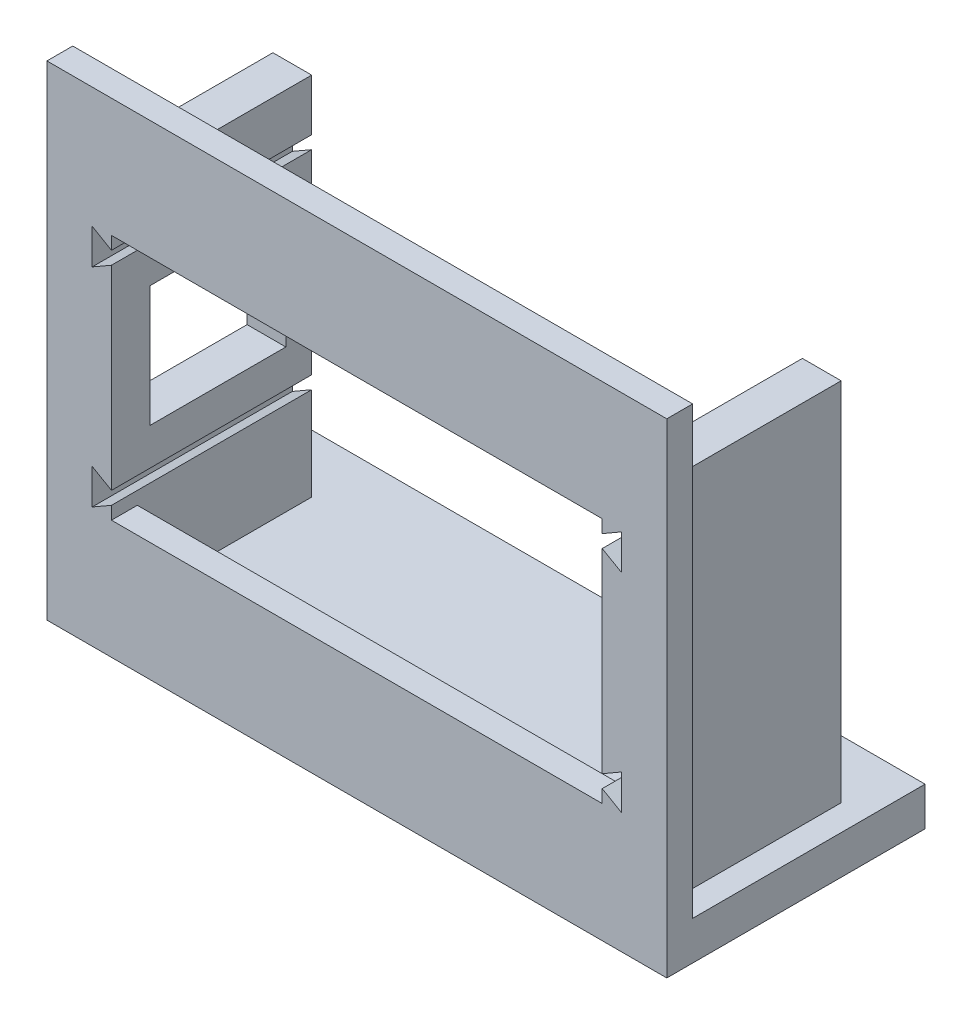
SolidWorks part; units mm, degrees
ref_plane "Front Plane" through (0, 0, 0) normal (0, 0, 1) x (1, 0, 0)
ref_plane "Top Plane" through (0, 0, 0) normal (0, 1, 0) x (1, 0, 0)
ref_plane "Right Plane" through (0, 0, 0) normal (1, 0, 0) x (0, 0, -1)
sketch "Sketch2" plane through (0, 0, 0) normal (0, 1, 0) x (1, 0, 0)
  line L1 (-100, 75) -> (100, 75)
  line L2 (-100, 75) -> (-100, -75)
  line L3 (-100, -75) -> (100, -75)
  line L4 (100, 75) -> (100, -75)
  line L5 (-100, 75) -> (100, -75) construction
  line L6 (-100, -75) -> (100, 75) construction
  point P0 (0, 0)
  dimension "D1" = 200
  dimension "D2" = 150
extrude "Boss-Extrude1" add sketch "Sketch2" along normal blind 80
fillet "Fillet1" radius 10 4 edges at (-100, 40, -75) (100, 40, -75) (100, 40, 75) (-100, 40, 75)
shell "Shell1" thickness 2
sketch "Sketch5" plane through (0, 0, 75) normal (0, 0, 1) x (1, 0, 0)
  line L1 (-18.25, 44.5) -> (18.25, 44.5)
  line L2 (-18.25, 44.5) -> (-18.25, 17)
  line L3 (-18.25, 17) -> (18.25, 17)
  line L4 (18.25, 44.5) -> (18.25, 17)
  line L5 (-18.25, 43.5) -> (-19.75, 44.366)
  line L6 (-19.75, 44.366) -> (-19.75, 41.634)
  line L7 (-19.75, 41.634) -> (-18.25, 42.5)
  line L8 (-18.25, 42.5) -> (-18.25, 43.5)
  line L9 (0, 44.5) -> (0, 17) construction
  line L10 (-18.25, 30.75) -> (18.25, 30.75) construction
  line L11 (-19.75, 19.866) -> (-18.25, 19)
  line L12 (-19.75, 17.134) -> (-19.75, 19.866)
  line L13 (-18.25, 18) -> (-19.75, 17.134)
  line L14 (-18.25, 19) -> (-18.25, 18)
  line L15 (19.75, 17.134) -> (19.75, 19.866)
  line L16 (18.25, 18) -> (19.75, 17.134)
  line L17 (18.25, 19) -> (18.25, 18)
  line L18 (19.75, 19.866) -> (18.25, 19)
  line L19 (19.75, 41.634) -> (18.25, 42.5)
  line L20 (19.75, 44.366) -> (19.75, 41.634)
  line L21 (18.25, 43.5) -> (19.75, 44.366)
  line L22 (18.25, 42.5) -> (18.25, 43.5)
  line L23 (-90, 15) -> (90, 15) construction
  point P4 (0, 17)
  dimension "D1" = 36.5
  dimension "D2" = 27.5
  dimension "D3" = 60
  dimension "D4" = 60
  dimension "D5" = 1
  dimension "D6" = 1
  dimension "D7" = 1.5
  dimension "D8" = 2
extrude "Cut-Extrude1" cut sketch "Sketch5" against normal up to surface (2 mm away) contours L1 L4 L3 L2 | L7 L8 L5 L6 | L12 L11 L14 L13 | L20 L19 L22 L21 | L15 L18 L17 L16 up to face at (0, 47.5, 73)
sketch "Sketch6" plane through (0, 0, 73) normal (0, 0, -1) x (-1, 0, 0)
  line L0 (18.25, 15) -> (21.25, 15)
  line L2 (-21.25, 47.5) -> (-21.25, 15)
  line L4 (19.75, 44.366) -> (18.25, 43.5)
  line L5 (19.75, 41.634) -> (19.75, 44.366)
  line L6 (18.25, 42.5) -> (19.75, 41.634)
  line L7 (18.25, 43.5) -> (18.25, 42.5)
  line L8 (19.75, 44.366) -> (18.25, 43.5)
  line L9 (19.75, 41.634) -> (19.75, 44.366)
  line L10 (18.25, 42.5) -> (19.75, 41.634)
  line L12 (18.25, 44.5) -> (-18.25, 44.5)
  line L13 (-18.25, 44.5) -> (-18.25, 17)
  line L14 (-18.25, 17) -> (18.25, 17)
  line L15 (18.25, 17) -> (18.25, 44.5)
  line L17 (-18.25, 47.5) -> (-18.25, 43.5)
  line L19 (18.25, 15) -> (18.25, 18)
  line L20 (-19.75, 41.634) -> (-18.25, 42.5)
  line L21 (-18.25, 42.5) -> (-18.25, 43.5)
  line L22 (-18.25, 43.5) -> (-19.75, 44.366)
  line L23 (-19.75, 44.366) -> (-19.75, 41.634)
  line L24 (-19.75, 41.634) -> (-18.25, 42.5)
  line L26 (-18.25, 43.5) -> (-19.75, 44.366)
  line L27 (-19.75, 44.366) -> (-19.75, 41.634)
  line L28 (-19.75, 19.866) -> (-19.75, 17.134)
  line L29 (-18.25, 19) -> (-19.75, 19.866)
  line L30 (-18.25, 18) -> (-18.25, 19)
  line L31 (-19.75, 17.134) -> (-18.25, 18)
  line L32 (-19.75, 19.866) -> (-19.75, 17.134)
  line L33 (-18.25, 19) -> (-19.75, 19.866)
  line L35 (-19.75, 17.134) -> (-18.25, 18)
  line L36 (19.75, 19.866) -> (18.25, 19)
  line L37 (18.25, 19) -> (18.25, 18)
  line L38 (18.25, 18) -> (19.75, 17.134)
  line L39 (19.75, 17.134) -> (19.75, 19.866)
  line L40 (19.75, 19.866) -> (18.25, 19)
  line L42 (18.25, 18) -> (19.75, 17.134)
  line L43 (19.75, 17.134) -> (19.75, 19.866)
  line L44 (21.25, 47.5) -> (21.25, 15)
  line L45 (-18.25, 15) -> (-21.25, 15)
  line L46 (-18.25, 42.5) -> (-18.25, 19)
  line L47 (18.25, 43.5) -> (18.25, 47.5)
  line L48 (18.25, 19) -> (18.25, 42.5)
  line L49 (-18.25, 18) -> (-18.25, 15)
  line L50 (21.25, 47.5) -> (18.25, 47.5)
  line L51 (-21.25, 47.5) -> (-18.25, 47.5)
  line L54 (18.25, 44.5) -> (-18.25, 44.5) construction
  line L55 (90, 15) -> (-90, 15) construction
  dimension "D6" = 3
  dimension "D7" = 3
  dimension "D8" = 3
  dimension "D1" = 0
  dimension "D2" = 0
  dimension "D3" = 0
  dimension "D4" = 0
  dimension "D5" = 0
extrude "Boss-Extrude2" add sketch "Sketch6" along normal blind 16
sketch "Sketch7" plane through (100, 0, 0) normal (1, 0, 0) x (0, 0, -1)
  line L0 (-65, 15) -> (65, 15) construction
  line L1 (-18.25, 44.5) -> (18.25, 44.5)
  line L2 (-18.25, 44.5) -> (-18.25, 17)
  line L3 (-18.25, 17) -> (18.25, 17)
  line L4 (18.25, 44.5) -> (18.25, 17)
  line L5 (-18.25, 43.5) -> (-19.75, 44.366)
  line L6 (-19.75, 44.366) -> (-19.75, 41.634)
  line L7 (-19.75, 41.634) -> (-18.25, 42.5)
  line L8 (-18.25, 42.5) -> (-18.25, 43.5)
  line L9 (0, 44.5) -> (0, 17) construction
  line L10 (-18.25, 30.75) -> (18.25, 30.75) construction
  line L11 (-19.75, 19.866) -> (-18.25, 19)
  line L12 (-19.75, 17.134) -> (-19.75, 19.866)
  line L13 (-18.25, 18) -> (-19.75, 17.134)
  line L14 (-18.25, 19) -> (-18.25, 18)
  line L15 (19.75, 17.134) -> (19.75, 19.866)
  line L16 (18.25, 18) -> (19.75, 17.134)
  line L17 (18.25, 19) -> (18.25, 18)
  line L18 (19.75, 19.866) -> (18.25, 19)
  line L19 (19.75, 41.634) -> (18.25, 42.5)
  line L20 (19.75, 44.366) -> (19.75, 41.634)
  line L21 (18.25, 43.5) -> (19.75, 44.366)
  line L22 (18.25, 42.5) -> (18.25, 43.5)
  dimension "D1" = 36.5
  dimension "D2" = 27.5
  dimension "D3" = 60
  dimension "D4" = 60
  dimension "D5" = 1
  dimension "D6" = 1
  dimension "D7" = 1.5
  dimension "D8" = 2
extrude "Cut-Extrude2" cut sketch "Sketch7" against normal blind 2 contours L1 L4 L3 L2 | L7 L8 L5 L6 | L12 L11 L14 L13 | L20 L19 L22 L21 | L15 L18 L17 L16
sketch "Sketch8" plane through (98, 0, 0) normal (-1, 0, 0) x (0, 0, 1)
  line L0 (65, 15) -> (-65, 15) construction
  line L1 (-21.25, 47.5) -> (-18.25, 47.5)
  line L2 (-21.25, 47.5) -> (-21.25, 15)
  line L3 (-21.25, 15) -> (-18.25, 15)
  line L4 (19.75, 44.366) -> (18.25, 43.5)
  line L5 (19.75, 41.634) -> (19.75, 44.366)
  line L6 (18.25, 42.5) -> (19.75, 41.634)
  line L7 (18.25, 43.5) -> (18.25, 42.5)
  line L8 (19.75, 44.366) -> (18.25, 43.5)
  line L9 (19.75, 41.634) -> (19.75, 44.366)
  line L10 (18.25, 42.5) -> (19.75, 41.634)
  line L20 (-19.75, 41.634) -> (-18.25, 42.5)
  line L21 (-18.25, 42.5) -> (-18.25, 43.5)
  line L22 (-18.25, 43.5) -> (-19.75, 44.366)
  line L23 (-19.75, 44.366) -> (-19.75, 41.634)
  line L24 (-19.75, 41.634) -> (-18.25, 42.5)
  line L26 (-18.25, 43.5) -> (-19.75, 44.366)
  line L27 (-19.75, 44.366) -> (-19.75, 41.634)
  line L28 (-19.75, 19.866) -> (-19.75, 17.134)
  line L29 (-18.25, 19) -> (-19.75, 19.866)
  line L30 (-18.25, 18) -> (-18.25, 19)
  line L31 (-19.75, 17.134) -> (-18.25, 18)
  line L32 (-19.75, 19.866) -> (-19.75, 17.134)
  line L33 (-18.25, 19) -> (-19.75, 19.866)
  line L35 (-19.75, 17.134) -> (-18.25, 18)
  line L36 (19.75, 19.866) -> (18.25, 19)
  line L37 (18.25, 19) -> (18.25, 18)
  line L38 (18.25, 18) -> (19.75, 17.134)
  line L39 (19.75, 17.134) -> (19.75, 19.866)
  line L40 (19.75, 19.866) -> (18.25, 19)
  line L42 (18.25, 18) -> (19.75, 17.134)
  line L43 (19.75, 17.134) -> (19.75, 19.866)
  line L44 (-18.25, 47.5) -> (-18.25, 43.5)
  line L46 (-18.25, 42.5) -> (-18.25, 19) construction
  line L47 (18.25, 44.5) -> (-18.25, 44.5) construction
  line L48 (-18.25, 42.5) -> (-18.25, 19)
  line L49 (-18.25, 18) -> (-18.25, 15)
  line L50 (18.25, 42.5) -> (18.25, 19) construction
  line L51 (18.25, 47.5) -> (21.25, 47.5)
  line L52 (18.25, 47.5) -> (18.25, 43.5)
  line L53 (18.25, 15) -> (21.25, 15)
  line L54 (21.25, 47.5) -> (21.25, 15)
  line L55 (18.25, 42.5) -> (18.25, 19)
  line L56 (18.25, 18) -> (18.25, 15)
  dimension "D6" = 3
  dimension "D7" = 3
  dimension "D2" = 3
  dimension "D1" = 0
  dimension "D3" = 0
  dimension "D4" = 0
  dimension "D5" = 0
extrude "Boss-Extrude3" add sketch "Sketch8" along normal blind 16
sketch "Sketch10" plane through (-100, 0, 0) normal (-1, 0, 0) x (0, 0, 1)
  line L1 (-18.25, 44.5) -> (18.25, 44.5)
  line L2 (-18.25, 44.5) -> (-18.25, 17)
  line L3 (-18.25, 17) -> (18.25, 17)
  line L4 (18.25, 44.5) -> (18.25, 17)
  line L5 (-18.25, 43.5) -> (-19.75, 44.366)
  line L6 (-19.75, 44.366) -> (-19.75, 41.634)
  line L7 (-19.75, 41.634) -> (-18.25, 42.5)
  line L8 (-18.25, 42.5) -> (-18.25, 43.5)
  line L9 (0, 44.5) -> (0, 17) construction
  line L10 (-18.25, 30.75) -> (18.25, 30.75) construction
  line L11 (-19.75, 19.866) -> (-18.25, 19)
  line L12 (-19.75, 17.134) -> (-19.75, 19.866)
  line L13 (-18.25, 18) -> (-19.75, 17.134)
  line L14 (-18.25, 19) -> (-18.25, 18)
  line L15 (19.75, 17.134) -> (19.75, 19.866)
  line L16 (18.25, 18) -> (19.75, 17.134)
  line L17 (18.25, 19) -> (18.25, 18)
  line L18 (19.75, 19.866) -> (18.25, 19)
  line L19 (19.75, 41.634) -> (18.25, 42.5)
  line L20 (19.75, 44.366) -> (19.75, 41.634)
  line L21 (18.25, 43.5) -> (19.75, 44.366)
  line L22 (18.25, 42.5) -> (18.25, 43.5)
  line L23 (-65, 15) -> (65, 15) construction
  dimension "D1" = 36.5
  dimension "D2" = 27.5
  dimension "D3" = 60
  dimension "D4" = 60
  dimension "D5" = 1
  dimension "D6" = 1
  dimension "D7" = 1.5
  dimension "D8" = 2
extrude "Cut-Extrude4" cut sketch "Sketch10" against normal blind 2 contours L1 L4 L3 L2 | L7 L8 L5 L6 | L12 L11 L14 L13 | L20 L19 L22 L21 | L15 L18 L17 L16
sketch "Sketch11" plane through (-98, 0, 0) normal (1, 0, 0) x (0, 0, -1)
  line L1 (-18.25, 42.5) -> (-18.25, 19) construction
  line L2 (-18.25, 47.5) -> (-21.25, 47.5)
  line L3 (-18.25, 47.5) -> (-18.25, 43.5)
  line L4 (19.75, 44.366) -> (18.25, 43.5)
  line L5 (19.75, 41.634) -> (19.75, 44.366)
  line L6 (18.25, 42.5) -> (19.75, 41.634)
  line L7 (18.25, 43.5) -> (18.25, 42.5)
  line L8 (19.75, 44.366) -> (18.25, 43.5)
  line L9 (19.75, 41.634) -> (19.75, 44.366)
  line L10 (18.25, 42.5) -> (19.75, 41.634)
  line L20 (-19.75, 41.634) -> (-18.25, 42.5)
  line L21 (-18.25, 42.5) -> (-18.25, 43.5)
  line L22 (-18.25, 43.5) -> (-19.75, 44.366)
  line L23 (-19.75, 44.366) -> (-19.75, 41.634)
  line L24 (-19.75, 41.634) -> (-18.25, 42.5)
  line L26 (-18.25, 43.5) -> (-19.75, 44.366)
  line L27 (-19.75, 44.366) -> (-19.75, 41.634)
  line L28 (-19.75, 19.866) -> (-19.75, 17.134)
  line L29 (-18.25, 19) -> (-19.75, 19.866)
  line L30 (-18.25, 18) -> (-18.25, 19)
  line L31 (-19.75, 17.134) -> (-18.25, 18)
  line L32 (-19.75, 19.866) -> (-19.75, 17.134)
  line L33 (-18.25, 19) -> (-19.75, 19.866)
  line L35 (-19.75, 17.134) -> (-18.25, 18)
  line L36 (19.75, 19.866) -> (18.25, 19)
  line L37 (18.25, 19) -> (18.25, 18)
  line L38 (18.25, 18) -> (19.75, 17.134)
  line L39 (19.75, 17.134) -> (19.75, 19.866)
  line L40 (19.75, 19.866) -> (18.25, 19)
  line L42 (18.25, 18) -> (19.75, 17.134)
  line L43 (19.75, 17.134) -> (19.75, 19.866)
  line L44 (-18.25, 15) -> (-21.25, 15)
  line L45 (-21.25, 47.5) -> (-21.25, 15)
  line L46 (65, 15) -> (-65, 15) construction
  line L47 (18.25, 44.5) -> (-18.25, 44.5) construction
  line L48 (-18.25, 42.5) -> (-18.25, 19)
  line L49 (-18.25, 18) -> (-18.25, 15)
  line L50 (18.25, 42.5) -> (18.25, 19) construction
  line L51 (18.25, 47.5) -> (21.25, 47.5)
  line L52 (18.25, 47.5) -> (18.25, 43.5)
  line L53 (18.25, 15) -> (21.25, 15)
  line L54 (21.25, 47.5) -> (21.25, 15)
  line L55 (18.25, 42.5) -> (18.25, 19)
  line L56 (18.25, 18) -> (18.25, 15)
  dimension "D2" = 3
  dimension "D6" = 3
  dimension "D7" = 3
  dimension "D1" = 0
  dimension "D3" = 0
  dimension "D4" = 0
  dimension "D5" = 0
extrude "Boss-Extrude4" add sketch "Sketch11" along normal blind 16
sketch "Sketch13" plane through (0, 0, 75) normal (0, 0, 1) x (1, 0, 0)
  line L0 (-18.25, 30.75) -> (18.25, 30.75) construction
  line L1 (-18.25, 30.75) -> (18.25, 30.75) construction
  line L2 (41, 39.3) -> (39.5, 40.166)
  line L3 (41, 40.3) -> (79, 40.3)
  line L4 (41, 40.3) -> (41, 21.2)
  line L5 (41, 21.2) -> (79, 21.2)
  line L6 (79, 40.3) -> (79, 21.2)
  line L7 (39.5, 40.166) -> (39.5, 37.434)
  line L8 (39.5, 37.434) -> (41, 38.3)
  line L9 (41, 39.3) -> (41, 38.3)
  line L10 (60, 40.3) -> (60, 21.2) construction
  line L11 (41, 22.2) -> (39.5, 21.334)
  line L12 (39.5, 21.334) -> (39.5, 24.066)
  line L13 (39.5, 24.066) -> (41, 23.2)
  line L14 (41, 22.2) -> (41, 23.2)
  line L15 (79, 22.2) -> (79, 23.2)
  line L16 (80.5, 24.066) -> (79, 23.2)
  line L17 (80.5, 21.334) -> (80.5, 24.066)
  line L18 (79, 22.2) -> (80.5, 21.334)
  line L19 (79, 39.3) -> (80.5, 40.166)
  line L20 (80.5, 40.166) -> (80.5, 37.434)
  line L21 (80.5, 37.434) -> (79, 38.3)
  line L22 (79, 39.3) -> (79, 38.3)
  point P6 (41, 30.75)
  point P7 (60, 21.2)
  dimension "D1" = 19.1
  dimension "D2" = 38
  dimension "D3" = 60
  dimension "D4" = 60
  dimension "D5" = 60
  dimension "D6" = 1
  dimension "D7" = 1
  dimension "D8" = 1.5
extrude "Cut-Extrude5" cut sketch "Sketch13" against normal up to surface (2 mm away) contours L3 L6 L5 L4 | L7 L8 L9 L2 | L12 L13 L14 L11 | L17 L16 L15 L18 | L20 L21 L22 L19 up to face at (0, 41.5833, 73)
sketch "Sketch14" plane through (0, 0, 73) normal (0, 0, -1) x (-1, 0, 0)
  line L0 (-21.25, 15) -> (-90, 15) construction
  line L1 (-79, 43.3) -> (-82, 43.3)
  line L2 (-79, 43.3) -> (-79, 39.3)
  line L3 (-79, 15) -> (-82, 15)
  line L6 (-82, 43.3) -> (-82, 15)
  line L12 (-39.5, 40.166) -> (-41, 39.3)
  line L13 (-39.5, 37.434) -> (-39.5, 40.166)
  line L14 (-41, 38.3) -> (-39.5, 37.434)
  line L15 (-41, 39.3) -> (-41, 38.3)
  line L16 (-39.5, 40.166) -> (-41, 39.3)
  line L17 (-39.5, 37.434) -> (-39.5, 40.166)
  line L18 (-41, 38.3) -> (-39.5, 37.434)
  line L20 (-79, 39.3) -> (-80.5, 40.166)
  line L21 (-80.5, 40.166) -> (-80.5, 37.434)
  line L22 (-80.5, 37.434) -> (-79, 38.3)
  line L23 (-79, 38.3) -> (-79, 39.3)
  line L24 (-79, 39.3) -> (-80.5, 40.166)
  line L25 (-80.5, 40.166) -> (-80.5, 37.434)
  line L26 (-80.5, 37.434) -> (-79, 38.3)
  line L28 (-79, 22.2) -> (-79, 23.2)
  line L29 (-79, 23.2) -> (-80.5, 24.066)
  line L30 (-80.5, 24.066) -> (-80.5, 21.334)
  line L31 (-80.5, 21.334) -> (-79, 22.2)
  line L33 (-79, 23.2) -> (-80.5, 24.066)
  line L34 (-80.5, 24.066) -> (-80.5, 21.334)
  line L35 (-80.5, 21.334) -> (-79, 22.2)
  line L36 (-39.5, 21.334) -> (-39.5, 24.066)
  line L37 (-39.5, 24.066) -> (-41, 23.2)
  line L38 (-41, 23.2) -> (-41, 22.2)
  line L39 (-41, 22.2) -> (-39.5, 21.334)
  line L40 (-39.5, 21.334) -> (-39.5, 24.066)
  line L41 (-39.5, 24.066) -> (-41, 23.2)
  line L43 (-41, 22.2) -> (-39.5, 21.334)
  line L44 (-41, 40.3) -> (-79, 40.3) construction
  line L45 (-41, 43.3) -> (-38, 43.3)
  line L46 (-41, 43.3) -> (-41, 39.3)
  line L47 (-41, 15) -> (-38, 15)
  line L48 (-38, 43.3) -> (-38, 15)
  line L49 (-79, 38.3) -> (-79, 23.2) construction
  line L50 (-41, 38.3) -> (-41, 23.2) construction
  line L51 (-79, 38.3) -> (-79, 23.2)
  line L52 (-79, 22.2) -> (-79, 15)
  line L53 (-41, 38.3) -> (-41, 23.2)
  line L54 (-41, 22.2) -> (-41, 15)
  dimension "D1" = 3
  dimension "D6" = 3
  dimension "D7" = 3
  dimension "D2" = 0
  dimension "D3" = 0
  dimension "D4" = 0
  dimension "D5" = 0
extrude "Boss-Extrude5" add sketch "Sketch14" along normal blind 13.5
sketch "Sketch15" plane through (38, 0, 0) normal (-1, 0, 0) x (0, 0, 1)
  line L4 (59.5, 15) -> (59.5, 43.3) construction
  line L5 (73, 15) -> (73, 43.3) construction
  line L6 (59.5, 43.3) -> (59.5, 15) construction
  line L7 (59.5, 37.434) -> (75, 37.434) construction
  line L8 (59.5, 24.066) -> (75, 24.066) construction
  line L12 (72, 26.066) -> (72, 35.434)
  line L13 (72, 35.434) -> (61.5, 35.434)
  line L14 (61.5, 35.434) -> (61.5, 26.066)
  line L15 (61.5, 26.066) -> (72, 26.066)
  dimension "D1" = 2
  dimension "D2" = 1
  dimension "D3" = 2
  dimension "D4" = 2
extrude "Cut-Extrude6" cut sketch "Sketch15" against normal up to surface (3 mm away) up to face at (41, 30.75, 67.25)
sketch "Sketch18" plane through (0, 0, 0) normal (1, 0, 0) x (0, 0, -1)
  line L0 (0, 0) -> (0, 10) construction
  line L3 (-42.5, 0) -> (-70, 0)
  line L4 (-70, 0) -> (-47.5, 10)
  line L5 (-47.5, 10) -> (-42.5, 10)
  line L6 (-42.5, 10) -> (-42.5, 0)
  line L7 (65, 0) -> (-65, 0) construction
  dimension "D1" = 10
  dimension "D2" = 70
  dimension "D3" = 5
  dimension "D4" = 42.5
revolve "Cut-Revolve1" cut sketch "Sketch18" angle 360 about L0
sketch "Sketch20" plane through (0, 0, 0) normal (0, -1, 0) x (1, 0, 0)
  circle A0 centre (0, -42.5) radius 8
  circle A1 centre (0, 0) radius 42.5 construction
  circle A2 centre (0, 0) radius 42.5 construction
  dimension "D1" = 16
extrude "Cut-Extrude8" cut sketch "Sketch20" against normal up to surface (15 mm away) up to face at (12, 15, 26.25)
sketch "Sketch21" plane through (0, 0, 75) normal (0, 0, 1) x (1, 0, 0)
  line L0 (41, 21.2) -> (79, 21.2) construction
  line L1 (36, 49.5) -> (84, 49.5)
  line L2 (36, 49.5) -> (36, 12)
  line L3 (36, 12) -> (84, 12)
  line L4 (84, 49.5) -> (84, 12)
  line L5 (36, 49.5) -> (84, 12) construction
  line L6 (36, 12) -> (84, 49.5) construction
  line L7 (41, 21.2) -> (79, 21.2) construction
  line L8 (41, 38.3) -> (41, 23.2) construction
  line L9 (41, 38.3) -> (41, 23.2) construction
  line L10 (79, 38.3) -> (79, 23.2) construction
  line L11 (41, 15) -> (79, 15) construction
  point P0 (60, 30.75)
  point P9 (0, 0)
  point P10 (60, 21.2)
  point P11 (0, 0)
  point P12 (41, 30.75)
  dimension "D1" = 5
  dimension "D2" = 3
split "Split1" trim tools "Sketch21" bodies to split 113 resulting bodies 114 115
sketch "Sketch22" plane through (0, 15, 0) normal (0, 1, 0) x (1, 0, 0)
  line L0 (36, -75) -> (84, -75) construction
  line L1 (36, -75) -> (84, -75)
  line L2 (36, -75) -> (36, -55)
  line L3 (36, -55) -> (84, -55)
  line L4 (84, -75) -> (84, -55)
  line L5 (84, -73) -> (84, -21.25) construction
  line L6 (36, 73) -> (36, -73) construction
  point P8 (36, -50.7511)
  dimension "D1" = 20
split "Split2" trim tools "Sketch22" bodies to split 114 resulting bodies 116 117
delete or keep bodies "Body-Delete/Keep 1" type delete bodies bodies 116 115
